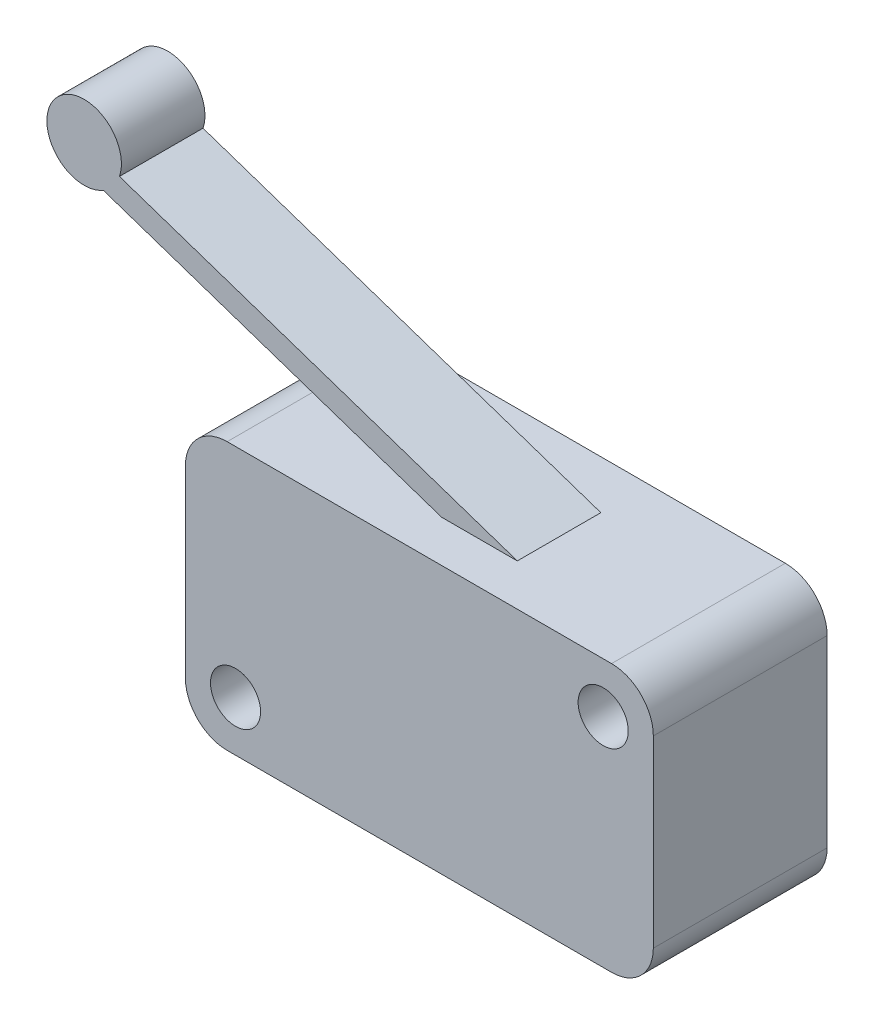
SolidWorks part; units mm, degrees
ref_plane "Płaszczyzna przednia" through (0, 0, 0) normal (0, 0, 1) x (1, 0, 0)
ref_plane "Płaszczyzna górna" through (0, 0, 0) normal (0, 1, 0) x (1, 0, 0)
ref_plane "Płaszczyzna prawa" through (0, 0, 0) normal (1, 0, 0) x (0, 0, -1)
sketch "Szkic1" plane through (0, 0, 0) normal (0, 0, 1) x (1, 0, 0)
  line L1 (0, 0) -> (28, 0)
  line L2 (0, 0) -> (0, 16)
  line L3 (0, 16) -> (28, 16)
  line L4 (28, 0) -> (28, 16)
  point P5 (0, 0)
extrude "Dodanie-wyciągnięcie1" add sketch "Szkic1" along normal blind 10.4
sketch "Szkic2" plane through (0, 0, 10.4) normal (0, 0, 1) x (1, 0, 0)
  circle A0 centre (3, 3) radius 1.5
  circle A1 centre (25, 13) radius 1.5
extrude "Wytnij-wyciągnięcie1" cut sketch "Szkic2" against normal blind 10.4
fillet "Zaokrąglenie1" radius 2.5 4 edges at (0, 0, 5.2) (0, 16, 5.2) (28, 16, 5.2) (28, 0, 5.2)
sketch "Szkic4" plane through (0, 0, 10.4) normal (0, 0, 1) x (1, 0, 0)
  line L0 (17.3602, 16) -> (-9.3745, 25.0068)
  line L1 (25.5, 16) -> (2.5, 16) construction
  line L2 (-9.3745, 25.0068) -> (-9.8358, 23.6377)
  line L3 (-9.8358, 23.6377) -> (15.2485, 15.1869)
  line L4 (15.2485, 15.1869) -> (17.3602, 16)
extrude "Dodanie-wyciągnięcie2" add sketch "Szkic4" against normal blind 5 from offset 2.5 offset against normal yes
sketch "Szkic5" plane through (0, 0, 7.9) normal (0, 0, 1) x (1, 0, 0)
  line L0 (17.3602, 16) -> (-9.3745, 25.0068) construction
  circle A0 centre (-8.56, 24.7323) radius 2.2292
extrude "Dodanie-wyciągnięcie3" add sketch "Szkic5" against normal blind 5
